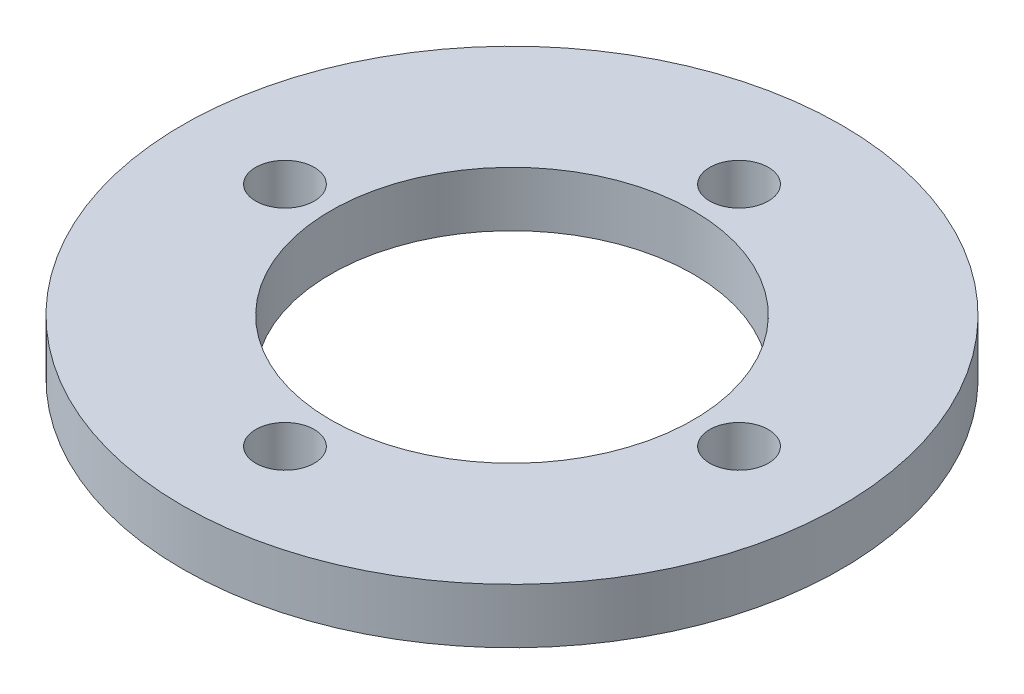
SolidWorks part; units mm, degrees
ref_plane "Front Plane" through (0, 0, 0) normal (0, 0, 1) x (1, 0, 0)
ref_plane "Top Plane" through (0, 0, 0) normal (0, 1, 0) x (1, 0, 0)
ref_plane "Right Plane" through (0, 0, 0) normal (1, 0, 0) x (0, 0, -1)
sketch "Sketch1" plane through (0, 0, 0) normal (0, 1, 0) x (1, 0, 0)
  circle A0 centre (0, 0) radius 9.9
  circle A1 centre (0, 0) radius 18
  circle A2 centre (0, 0) radius 12.4 construction
  circle A3 centre (0, 12.4) radius 1.6
  circle A4 centre (12.4, 0) radius 1.6
  circle A5 centre (0, -12.4) radius 1.6
  circle A6 centre (-12.4, 0) radius 1.6
  point P7 (12.4, 0)
  point P16 (0, 0)
  dimension "D1" = 19.8
  dimension "D2" = 36
  dimension "D3" = 24.8
  dimension "D4" = 3.2
  dimension "D5" = 4
extrude "Boss-Extrude1" add sketch "Sketch1" along normal blind 3
